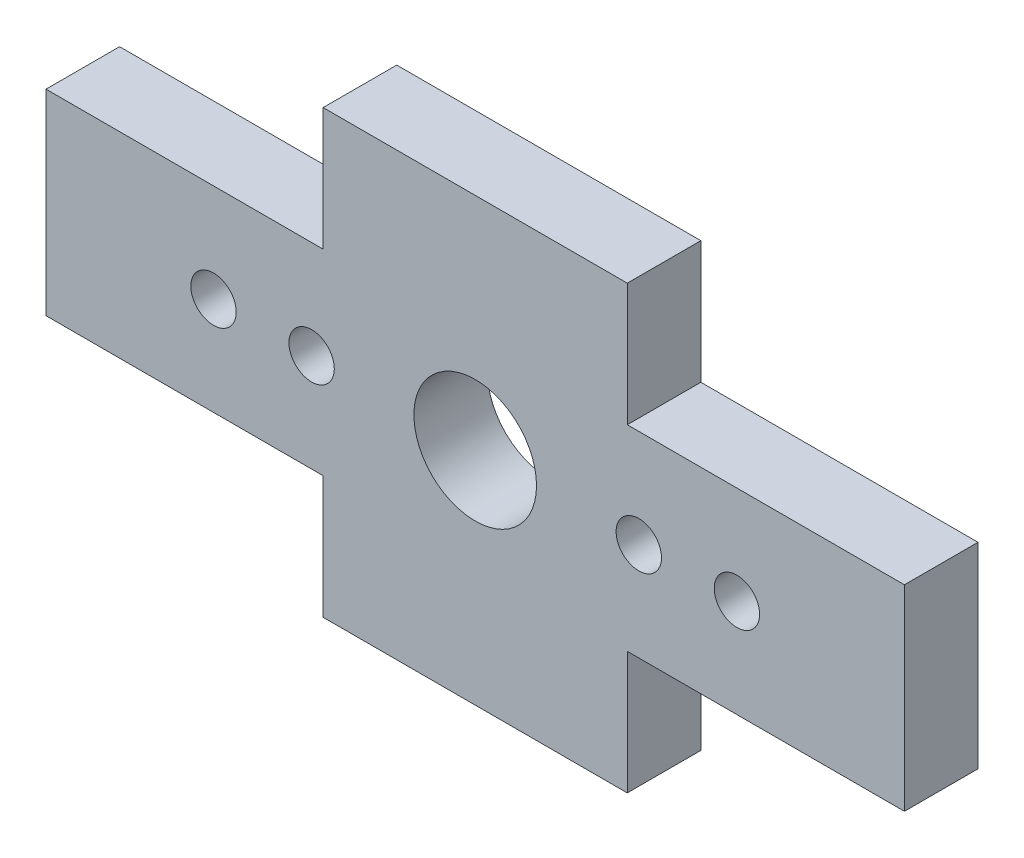
SolidWorks part; units mm, degrees
ref_plane "Plan de face" through (0, 0, 0) normal (0, 0, 1) x (1, 0, 0)
ref_plane "Plan de dessus" through (0, 0, 0) normal (0, 1, 0) x (1, 0, 0)
ref_plane "Plan de droite" through (0, 0, 0) normal (1, 0, 0) x (0, 0, -1)
sketch "Esquisse1" plane through (0, 0, 0) normal (0, 0, 1) x (1, 0, 0)
  line L0 (-17.5, -4) -> (-17.5, 4)
  line L2 (-6.2, -4) -> (-6.2, -9)
  line L3 (-6.2, 4) -> (-6.2, 9)
  line L4 (17.5, -4) -> (6.2, -4)
  line L5 (-6.2, -4) -> (-17.5, -4)
  line L6 (-17.5, 4) -> (-6.2, 4)
  line L7 (6.2, 4) -> (17.5, 4)
  line L8 (6.2, -4) -> (6.2, -9)
  line L9 (6.2, 4) -> (6.2, 9)
  line L11 (17.5, 4) -> (17.5, -4)
  line L12 (-6.2, 9) -> (6.2, 9)
  line L13 (-6.2, -9) -> (6.2, -9)
  circle A0 centre (0, 0) radius 2.5
  circle A1 centre (6.67, 0) radius 0.925
  circle A2 centre (10.67, 0) radius 0.925
  circle A3 centre (-6.67, 0) radius 0.925
  circle A4 centre (-10.67, 0) radius 0.925
  dimension "D3" = 13.34
  dimension "D4" = 21.34
  dimension "D5" = 5
  dimension "D6" = 1.85
  dimension "D1" = 6.67
  dimension "D2" = 10.67
  dimension "D7" = 18
  dimension "D8" = 8
  dimension "D9" = 4
  dimension "D10" = 9
  dimension "D11" = 35
  dimension "D12" = 17.5
  dimension "D13" = 12.4
  dimension "D14" = 6.2
extrude "Boss.-Extru.1" add sketch "Esquisse1" along normal blind 3
